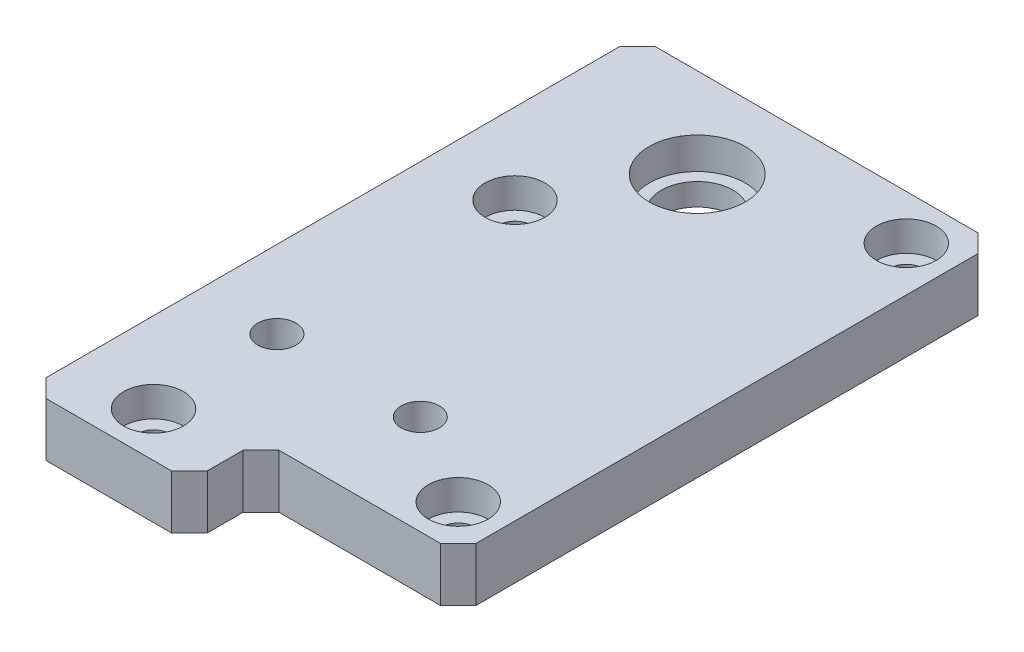
SolidWorks part; units mm, degrees
material "PET"
ref_plane "Front Plane" through (0, 0, 0) normal (0, 0, 1) x (1, 0, 0)
ref_plane "Top Plane" through (0, 0, 0) normal (0, 1, 0) x (1, 0, 0)
ref_plane "Right Plane" through (0, 0, 0) normal (1, 0, 0) x (0, 0, -1)
sketch "Sketch1" plane through (0, 0, 0) normal (0, 1, 0) x (1, 0, 0)
  line L1 (2, -45) -> (35, -45)
  line L3 (-25, 45) -> (35, 45)
  line L4 (35, -45) -> (35, 45)
  line L5 (-25, -57) -> (2, -57)
  line L6 (2, -57) -> (2, -45)
  line L7 (-25, 45) -> (-25, -57)
  point P0 (0, 0)
  dimension "D1" = 60
  dimension "D2" = 90
  dimension "D3" = 35
  dimension "D4" = 45
  dimension "D5" = 12
  dimension "D6" = 27
extrude "Boss-Extrude1" add sketch "Sketch1" along normal blind 9
sketch "Sketch4" plane through (0, 9, 0) normal (0, 1, 0) x (1, 0, 0)
  line L3 (35, -45) -> (35, 45) construction
  line L4 (2, -45) -> (35, -45) construction
  line L5 (35, 45) -> (-25, 45) construction
  line L6 (-25, -57) -> (2, -57) construction
  point P4 (27.5, 37.5)
  point P6 (27.5, -37.5)
  point P23 (-11.5, 11)
  point P25 (-11.5, -49.5)
  point P32 (-11.5, -57)
  dimension "D1" = 7.5
  dimension "D2" = 49.5
  dimension "D3" = 7.5
  dimension "D4" = 7.5
  dimension "D5" = 11
hole_wizard "CBORE for M5 SHCS1" positions "Sketch4" profile "Sketch3" counterbore size "M5" standard "ANSI Metric" end condition through all
sketch "Sketch3" plane through (27.5, 9, -37.5) normal (1, 0, 0) x (0, 0, 1)
  line L0 (0, 0) -> (0, 9)
  line L1 (0, 9) -> (2.75, 9)
  line L3 (2.75, 9) -> (2.75, 5)
  line L4 (2.75, 5) -> (5, 5)
  line L5 (5, 5) -> (5, 0)
  line L7 (5, 0) -> (0, 0)
  line L11 (0, -6.35) -> (0, 107.95) construction
  dimension "Thru Hole Dia." = 5.5
  dimension "Thru Hole Depth" = 9
  dimension "C'Bore Dia." = 10
  dimension "C'Bore Depth" = 5
sketch "Sketch7" plane through (0, 9, 0) normal (0, 1, 0) x (1, 0, 0)
  line L0 (35, 45) -> (-25, 45) construction
  point P0 (0, 30)
  dimension "D1" = 15
hole_wizard "Ø1.0mm Dowel Hole1" positions "Sketch7" profile "Sketch6" hole size "Ø1.0" standard "ANSI Metric"
sketch "Sketch6" plane through (0, 9, -30) normal (1, 0, 0) x (0, 0, 1)
  line L0 (0, 0) -> (0, 5.3)
  line L1 (0, 5.3) -> (8.05, 5.3)
  line L2 (8.05, 5.3) -> (8.05, 0)
  line L5 (8.05, 0) -> (0, 0)
  line L10 (0, 5.3) -> (-8.05, 5.3) construction
  line L11 (0, -6.35) -> (0, 107.95) construction
  dimension "Hole Dia." = 16.1
  dimension "Hole Depth" = 5.3
  dimension "Drill Angle" = 180
sketch "Sketch13" plane through (0, 3.7, 0) normal (0, 1, 0) x (1, 0, 0)
  point P0 (0, 30)
hole_wizard "Ø1.0mm Dowel Hole3" positions "Sketch13" profile "Sketch12" hole size "Ø1.0" standard "ANSI Metric" end condition through all
sketch "Sketch12" plane through (0, 3.7, -30) normal (1, 0, 0) x (0, 0, 1)
  line L0 (0, 0) -> (0, 3.7)
  line L1 (0, 3.7) -> (6, 3.7)
  line L2 (6, 3.7) -> (6, 0)
  line L5 (6, 0) -> (0, 0)
  line L11 (0, -6.35) -> (0, 107.95) construction
  dimension "Thru Hole Dia." = 12
  dimension "Thru Hole Depth" = 3.7
sketch "Sketch14" plane through (0, 9, 0) normal (0, 1, 0) x (1, 0, 0)
  circle A2 centre (12, -28.35) radius 3.2
  circle A3 centre (-12, -28.35) radius 3.2
  dimension "D5" = 6.4
  dimension "D6" = 6.4
  dimension "D1" = 28.35
  dimension "D2" = 12
  dimension "D3" = 12
  dimension "D4" = 28.35
extrude "Cut-Extrude1" cut sketch "Sketch14" against normal through all
chamfer "Chamfer1" distance 3 angle 45 6 edges at (35, 4.5, -45) (35, 4.5, 45) (2, 4.5, 45) (2, 4.5, 57) (-25, 4.5, 57) (-25, 4.5, -45)
equation "\"D4@Sketch14\"=\"D1@Sketch14\""
equation "\"D4@Sketch1\"=0.5*\"D2@Sketch1\""
